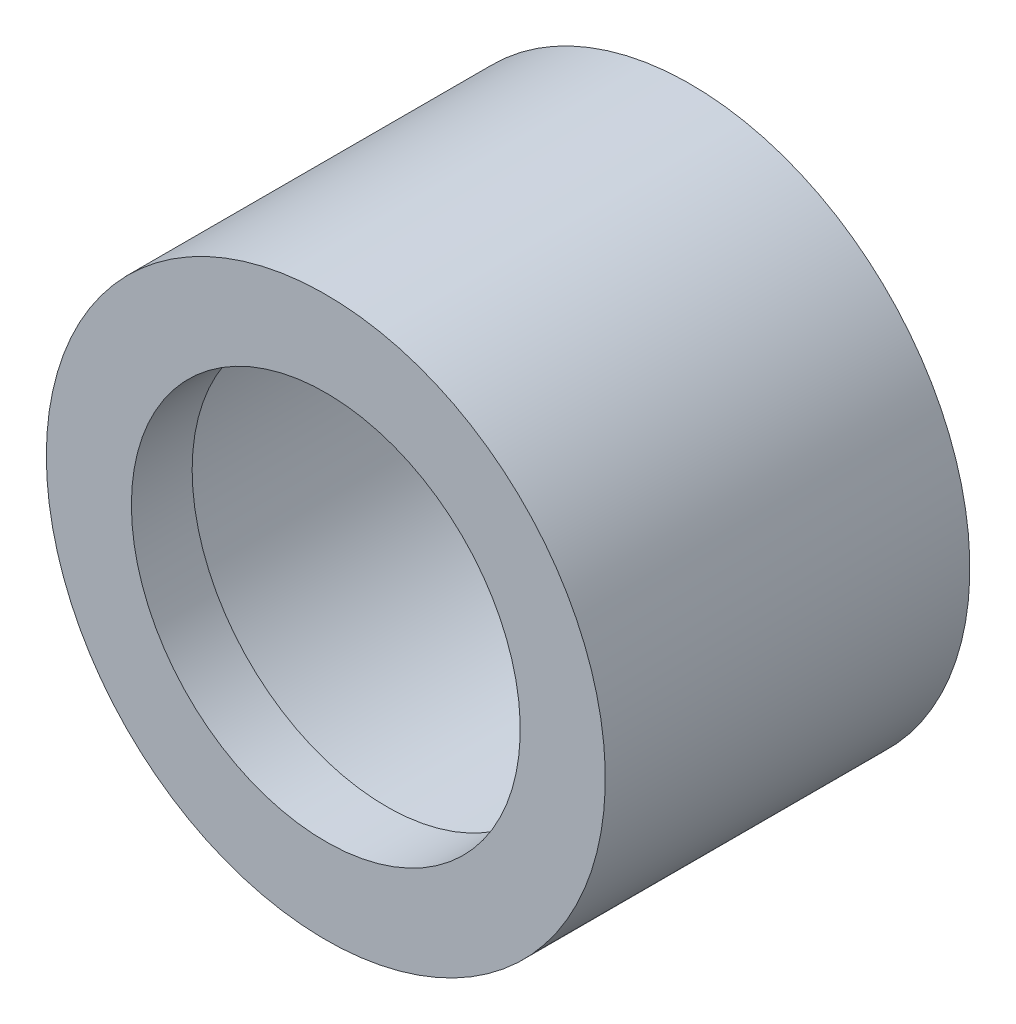
SolidWorks part; units mm, degrees
ref_plane "Front Plane" through (0, 0, 0) normal (0, 0, 1) x (1, 0, 0)
ref_plane "Top Plane" through (0, 0, 0) normal (0, 1, 0) x (1, 0, 0)
ref_plane "Right Plane" through (0, 0, 0) normal (1, 0, 0) x (0, 0, -1)
ref_axis "Axis1" through (0, 0, -55.9602) along (0, 0, 1)
sketch "Sketch1" plane through (0, 0, 0) normal (0, 1, 0) x (1, 0, 0)
  line L0 (-11.5, 15) -> (-11.5, 0)
  line L1 (-44.2539, 0) -> (44.2539, 0) construction
  line L2 (-11.5, 0) -> (-8, 0)
  line L3 (-8, 0) -> (-8, 2.5)
  line L4 (-8, 2.5) -> (-9.5, 2.5)
  line L5 (-9.5, 2.5) -> (-9.5, 15)
  line L6 (-9.5, 15) -> (-11.5, 15)
  line L7 (0, -44.7868) -> (0, 44.7868) construction
  dimension "D1" = 12.5
  dimension "D2" = 2.5
  dimension "D3" = 9.5
  dimension "D4" = 1.5
  dimension "D5" = 2
revolve "Revolve1" add sketch "Sketch1" angle 360 about axis through (0, 0, -55.9602) along (0, 0, 1)
